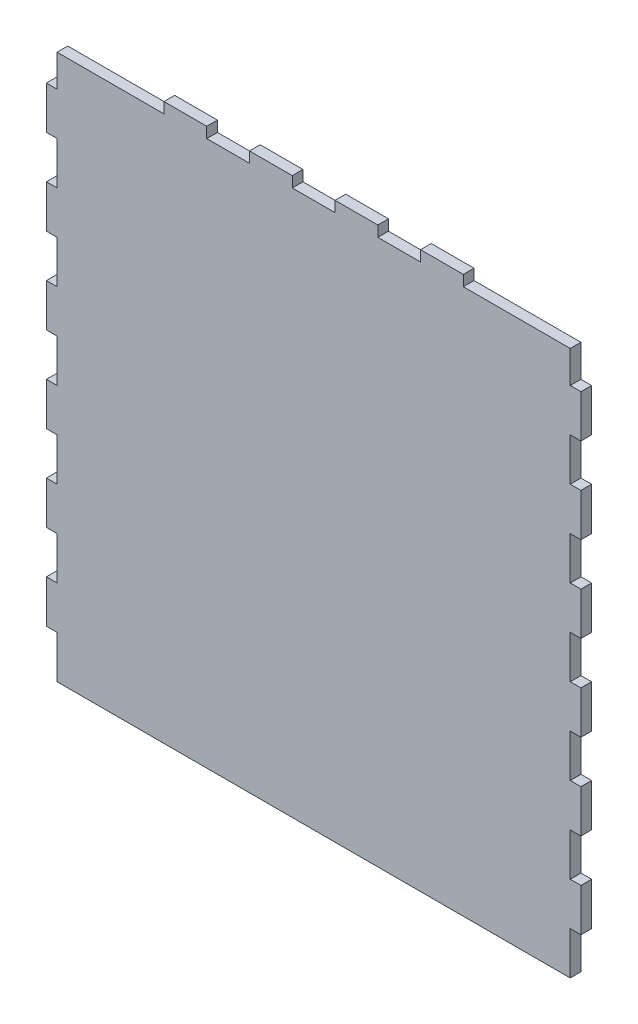
SolidWorks part; units mm, degrees
ref_plane "Front Plane" through (0, 0, 0) normal (0, 0, 1) x (1, 0, 0)
ref_plane "Top Plane" through (0, 0, 0) normal (0, 1, 0) x (1, 0, 0)
ref_plane "Right Plane" through (0, 0, 0) normal (1, 0, 0) x (0, 0, -1)
sketch "Sketch1" plane through (0, 0, 0) normal (0, 0, 1) x (1, 0, 0)
  line L0 (-76.2, 82.55) -> (-76.2, 69.85)
  line L1 (-76.2, -82.55) -> (76.2, -82.55)
  line L3 (-76.2, 82.55) -> (76.2, 82.55)
  line L5 (-109.6257, -118.7612) -> (76.2, 82.55) construction
  line L6 (-87.6243, 94.9263) -> (76.2, -82.55) construction
  line L7 (-76.2, 69.85) -> (-79.375, 69.85)
  line L8 (-79.375, 69.85) -> (-79.375, 57.15)
  line L9 (-79.375, 57.15) -> (-76.2, 57.15)
  line L10 (-76.2, 57.15) -> (-76.2, 44.45)
  line L11 (-76.2, 44.45) -> (-79.375, 44.45)
  line L12 (-79.375, 44.45) -> (-79.375, 31.75)
  line L13 (-79.375, 31.75) -> (-76.2, 31.75)
  line L14 (-76.2, 31.75) -> (-76.2, 19.05)
  line L15 (-76.2, 19.05) -> (-79.375, 19.05)
  line L16 (-79.375, 19.05) -> (-79.375, 6.35)
  line L17 (-79.375, 6.35) -> (-76.2, 6.35)
  line L18 (-76.2, 6.35) -> (-76.2, -6.35)
  line L19 (-76.2, -6.35) -> (-79.375, -6.35)
  line L20 (-79.375, -6.35) -> (-79.375, -19.05)
  line L21 (-79.375, -19.05) -> (-76.2, -19.05)
  line L22 (-76.2, -19.05) -> (-76.2, -31.75)
  line L23 (-76.2, -31.75) -> (-79.375, -31.75)
  line L24 (-79.375, -31.75) -> (-79.375, -44.45)
  line L25 (-79.375, -44.45) -> (-76.2, -44.45)
  line L26 (-76.2, -44.45) -> (-76.2, -57.15)
  line L27 (-76.2, -57.15) -> (-79.375, -57.15)
  line L28 (-79.375, -57.15) -> (-79.375, -69.85)
  line L29 (-79.375, -69.85) -> (-76.2, -69.85)
  line L30 (-76.2, -69.85) -> (-76.2, -82.55)
  line L31 (0, 82.55) -> (0, -82.55) construction
  line L32 (76.2, -69.85) -> (76.2, -82.55)
  line L33 (79.375, -69.85) -> (76.2, -69.85)
  line L34 (79.375, -57.15) -> (79.375, -69.85)
  line L35 (76.2, -57.15) -> (79.375, -57.15)
  line L36 (76.2, -44.45) -> (76.2, -57.15)
  line L37 (79.375, -44.45) -> (76.2, -44.45)
  line L38 (79.375, -31.75) -> (79.375, -44.45)
  line L39 (76.2, -31.75) -> (79.375, -31.75)
  line L40 (76.2, -19.05) -> (76.2, -31.75)
  line L41 (79.375, -19.05) -> (76.2, -19.05)
  line L42 (79.375, -6.35) -> (79.375, -19.05)
  line L43 (76.2, -6.35) -> (79.375, -6.35)
  line L44 (76.2, 6.35) -> (76.2, -6.35)
  line L45 (79.375, 6.35) -> (76.2, 6.35)
  line L46 (79.375, 19.05) -> (79.375, 6.35)
  line L47 (76.2, 19.05) -> (79.375, 19.05)
  line L48 (76.2, 31.75) -> (76.2, 19.05)
  line L49 (79.375, 31.75) -> (76.2, 31.75)
  line L50 (79.375, 44.45) -> (79.375, 31.75)
  line L51 (76.2, 44.45) -> (79.375, 44.45)
  line L52 (76.2, 57.15) -> (76.2, 44.45)
  line L53 (79.375, 57.15) -> (76.2, 57.15)
  line L54 (79.375, 69.85) -> (79.375, 57.15)
  line L55 (76.2, 69.85) -> (79.375, 69.85)
  line L56 (76.2, 82.55) -> (76.2, 69.85)
  point P0 (0, 0)
  dimension "D1" = 12.7
  dimension "D2" = 3.175
  dimension "D3" = 12.7
  dimension "D4" = 165.1
  dimension "D5" = 76.2
extrude "Boss-Extrude1" add sketch "Sketch1" along normal mid plane 3.175
sketch "Sketch2" plane through (0, 82.55, 0) normal (0, 1, 0) x (1, 0, 0)
  line L0 (76.2, -1.5875) -> (44.45, -1.5875)
  line L1 (-76.2, -1.5875) -> (-76.2, 1.5875)
  line L2 (-76.2, 1.5875) -> (-44.45, 1.5875)
  line L3 (76.2, 1.5875) -> (76.2, -1.5875)
  line L4 (44.45, 1.5875) -> (44.45, -1.5875)
  line L5 (44.45, 1.5875) -> (44.45, -1.5875) construction
  line L6 (31.75, 1.5875) -> (31.75, -1.5875)
  line L7 (19.05, 1.5875) -> (19.05, -1.5875)
  line L8 (19.05, 1.5875) -> (19.05, -1.5875) construction
  line L9 (6.35, 1.5875) -> (6.35, -1.5875)
  line L10 (6.35, -1.5875) -> (6.35, 1.5875) construction
  line L11 (-6.35, 1.5875) -> (-6.35, -1.5875)
  line L12 (-6.35, 1.5875) -> (-6.35, -1.5875) construction
  line L13 (-19.05, 1.5875) -> (-19.05, -1.5875)
  line L14 (-19.05, -1.5875) -> (-19.05, 1.5875) construction
  line L15 (-31.75, 1.5875) -> (-31.75, -1.5875)
  line L16 (-31.75, 1.5875) -> (-31.75, -1.5875) construction
  line L17 (-44.45, 1.5875) -> (-44.45, -1.5875)
  line L18 (-44.45, -1.5875) -> (-44.45, 1.5875) construction
  line L19 (31.75, -1.5875) -> (31.75, 1.5875) construction
  line L20 (31.75, -1.5875) -> (19.05, -1.5875)
  line L21 (44.45, 1.5875) -> (76.2, 1.5875)
  line L22 (6.35, -1.5875) -> (-6.35, -1.5875)
  line L23 (19.05, 1.5875) -> (31.75, 1.5875)
  line L24 (-19.05, -1.5875) -> (-31.75, -1.5875)
  line L25 (-6.35, 1.5875) -> (6.35, 1.5875)
  line L26 (-44.45, -1.5875) -> (-76.2, -1.5875)
  line L27 (-31.75, 1.5875) -> (-19.05, 1.5875)
extrude "Cut-Extrude1" cut sketch "Sketch2" against normal blind 3.175
